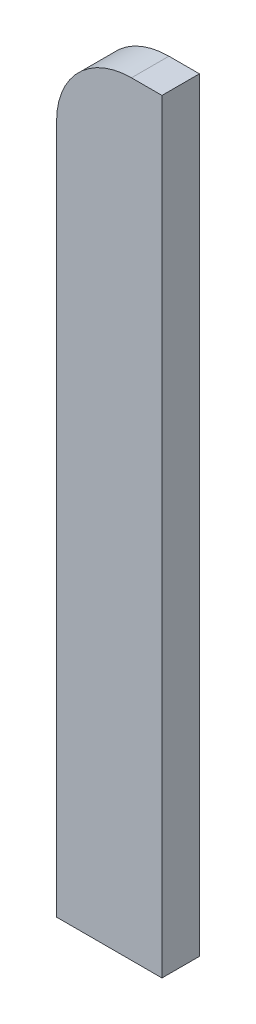
SolidWorks part; units mm, degrees
material "POLYURETHANE (11671)"
ref_plane "Front Plane" through (0, 0, 0) normal (0, 0, 1) x (1, 0, 0)
ref_plane "Top Plane" through (0, 0, 0) normal (0, 1, 0) x (1, 0, 0)
ref_plane "Right Plane" through (0, 0, 0) normal (1, 0, 0) x (0, 0, -1)
sketch "Sketch1" plane through (0, 0, 0) normal (0, 0, 1) x (1, 0, 0)
  line L0 (0, 0) -> (28.144, 0) construction
  line L3 (21.108, 67.481) -> (21.108, 169.54)
  line L4 (21.108, 169.54) -> (7.036, 169.54)
  line L5 (7.036, 169.54) -> (7.036, 67.481)
  line L8 (7.036, 67.481) -> (21.108, 67.481)
  point P3 (14.072, 0)
  point P4 (14.072, 67.481)
  dimension "D3" = 169.54
  dimension "D7" = 14.072
  dimension "D4" = 67.481
  dimension "D1" = 28.144
extrude "Boss-Extrude1" add sketch "Sketch1" along normal blind 5 contours L3 L4 L5 L8
fillet "Fillet1" radius 10 1 edges at (7.036, 169.54, 2.5)
equation "\"B1\"=0.028144"
equation "\"B2\"=0.014072"
equation "\"B3\"=0.066845"
equation "\"H1\"=0.033908"
equation "\"H2\"=0.055948"
equation "\"H3\"=0.147500"
equation "\"H4\"=0.169540"
equation "\"T\"=0.005000"
equation "\"L\"=0.019701"
equation "\"bolt_hole_diameter\"=0.003400"
equation "\"D3@Sketch1\"=\"H4\"*1000"
equation "\"D7@Sketch1\"=\"B2\"*1000"
equation "\"spring_arm_hole_pos\"=0.007880"
equation "\"H_holes\"=0.006332"
equation "\"spring_arm_hole_max_diam\"=0.006000"
equation "\"spring_arm_hole_min_diam\"=0.003400"
equation "\"arm_hole_head_height\"=0.001650"
equation "\"D_strap\"=0.071845"
equation "\"clip_hole_D\"=0.003400"
equation "\"clip_hole_y1\"=0.007500"
equation "\"clip_hole_dist\"=0.015000"
equation "\"pad_t1\"=0.005000"
equation "\"pad_t2\"=0.000000"
equation "\"unpad_L1\"=0.067481"
equation "\"D4@Sketch1\"=\"unpad_L1\"*1000"
equation "\"D1@Sketch1\"=\"B1\"*1000"
equation "\"D1@Boss-Extrude1\"=\"pad_t1\"*1000"
